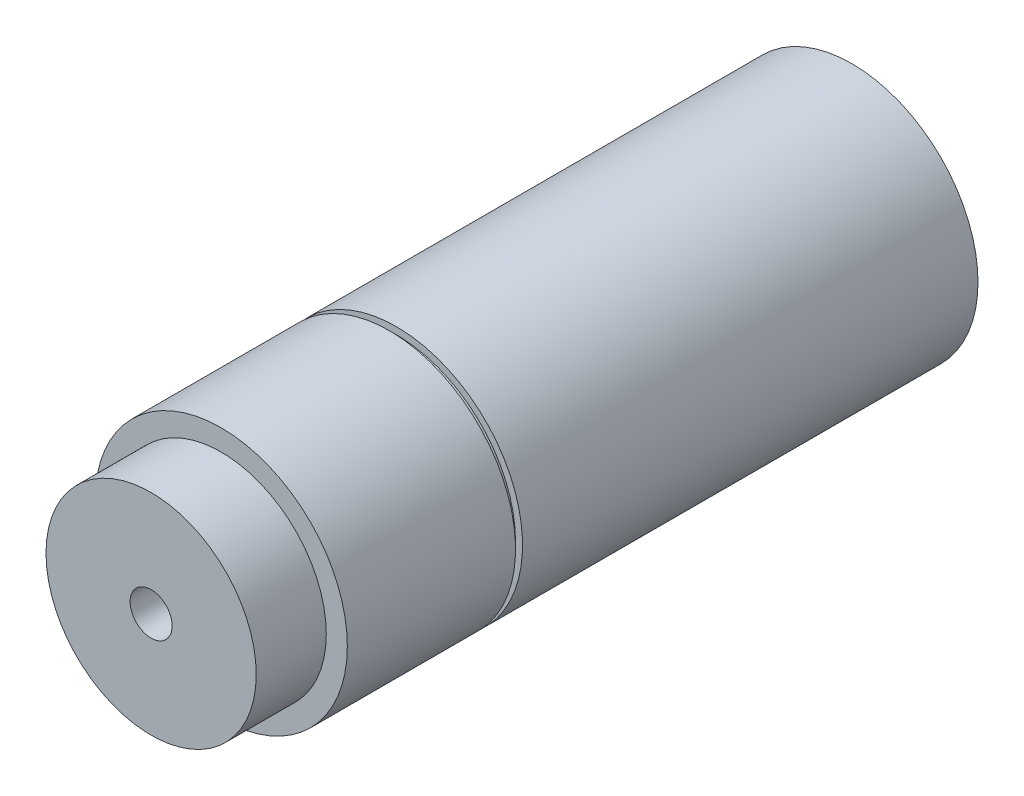
SolidWorks part; units mm, degrees
material "Alloy Steel"
ref_plane "Front Plane" through (0, 0, 0) normal (0, 0, 1) x (1, 0, 0)
ref_plane "Top Plane" through (0, 0, 0) normal (0, 1, 0) x (1, 0, 0)
ref_plane "Right Plane" through (0, 0, 0) normal (1, 0, 0) x (0, 0, -1)
sketch "Sketch1" plane through (0, 0, 0) normal (0, 0, 1) x (1, 0, 0)
  circle A0 centre (0, 0) radius 18
  dimension "D1" = 36
extrude "Boss-Extrude1" add sketch "Sketch1" along normal blind 100
sketch "Sketch2" plane through (0, 0, 100) normal (0, 0, 1) x (1, 0, 0)
  circle A0 centre (0, 0) radius 15
  circle A1 centre (0, 0) radius 25
  dimension "D1" = 30
extrude "Cut-Extrude2" cut sketch "Sketch2" against normal blind 10
sketch "Sketch4" plane through (0, 0, 100) normal (0, 0, 1) x (1, 0, 0)
  circle A0 centre (0, 0) radius 3
  dimension "D1" = 6
extrude "Cut-Extrude3" cut sketch "Sketch4" against normal blind 100 contours A0
ref_plane "Plane1" through (0, 0, 65) normal (0, 0, -1) x (-1, 0, 0)
sketch "Sketch5" plane through (0, 0, 65) normal (0, 0, -1) x (-1, 0, 0)
  circle A0 centre (0, 0) radius 18
  circle A1 centre (0, 0) radius 17
  dimension "D1" = 36
  dimension "D2" = 34
extrude "Cut-Extrude4" cut sketch "Sketch5" against normal blind 1
